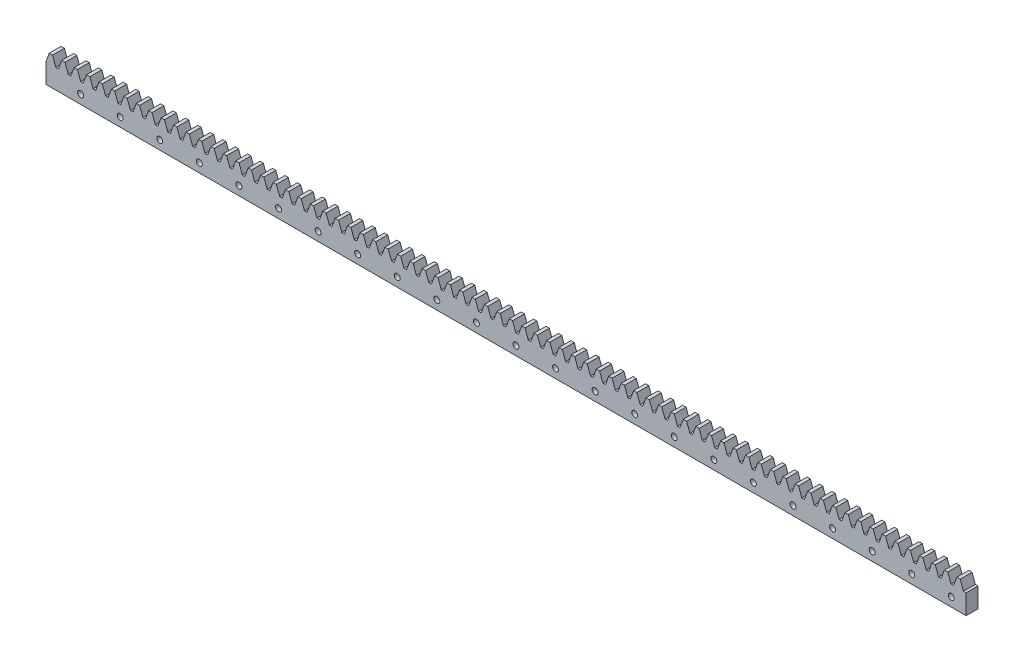
SolidWorks part; units mm, degrees
material "Thornel Mat VMA"
ref_plane "前视基准面" through (0, 0, 0) normal (0, 0, 1) x (1, 0, 0)
ref_plane "上视基准面" through (0, 0, 0) normal (0, 1, 0) x (1, 0, 0)
ref_plane "右视基准面" through (0, 0, 0) normal (1, 0, 0) x (0, 0, -1)
sketch "草图1" plane through (0, 0, 0) normal (0, 0, 1) x (1, 0, 0)
  line L1 (0, 0) -> (465, 0)
  line L2 (0, 0) -> (0, -10)
  line L3 (0, -10) -> (465, -10)
  line L4 (465, 0) -> (465, -10)
  dimension "D1" = 10
  dimension "L" = 465
extrude "拉伸1" add sketch "草图1" along normal blind 6
sketch "草图2" plane through (0, 0, 6) normal (0, 0, 1) x (1, 0, 0)
  line L0 (0, 0) -> (1.6379, 4.5)
  line L1 (1.6379, 4.5) -> (3.3236, 4.5)
  line L2 (3.3236, 4.5) -> (4.9614, 0)
  line L3 (465, 0) -> (0, 0) construction
  line L4 (0, 0) -> (4.9614, 0)
  line L5 (0.9099, 2.5) -> (4.0515, 2.5) construction
  dimension "D2" = 70
  dimension "alpha" = 110
  dimension "ha" = 2
  dimension "hf" = 2.5
  dimension "S" = 3.1416
extrude "拉伸2" add sketch "草图2" against normal up to surface (6 mm away) up to face at (232.5, -5, 0)
pattern_linear "阵列(线性)1" count 74 spacing 6.2832 along (1, 0, 0) of "拉伸2"
sketch "草图3" plane through (0, 0, 6) normal (0, 0, 1) x (1, 0, 0)
  circle A0 centre (457.5, -5.5) radius 3 construction
  circle A1 centre (457.5, -5.5) radius 3 construction
  circle A2 centre (457.5, -5.5) radius 1.5
  dimension "D1" = 3
extrude "切除-拉伸1" cut sketch "草图3" against normal blind 10
pattern_linear "阵列(线性)2" count 24 spacing 20 along (-1, 0, 0) of "切除-拉伸1"
equation "\"d\"=\"S@草图2\" * 2"
equation "\"z\"= int(  \"L@草图1\" / (  \"S@草图2\" * 2 ) + 0.5 )"
